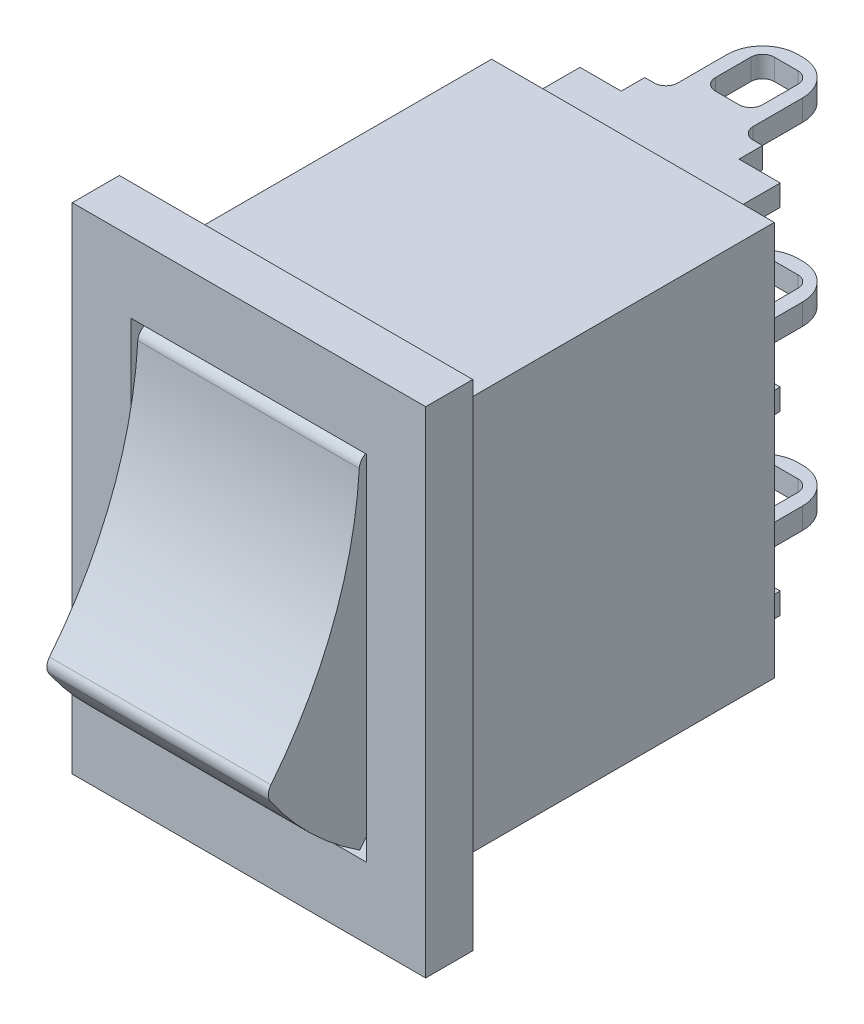
SolidWorks part; units mm, degrees
ref_plane "Frontal" through (0, 0, 0) normal (0, 0, 1) x (1, 0, 0)
ref_plane "Superior" through (0, 0, 0) normal (0, 1, 0) x (1, 0, 0)
ref_plane "Direito" through (0, 0, 0) normal (1, 0, 0) x (0, 0, -1)
sketch "Esboço1" plane through (0, 0, 0) normal (0, 0, 1) x (1, 0, 0)
  line L1 (-6, 8.375) -> (6, 8.375)
  line L2 (-6, 8.375) -> (-6, -8.375)
  line L3 (-6, -8.375) -> (6, -8.375)
  line L4 (6, 8.375) -> (6, -8.375)
  line L5 (-6, 8.375) -> (6, -8.375) construction
  line L6 (-6, -8.375) -> (6, 8.375) construction
  point P0 (0, 0)
  dimension "D1" = 16.75
  dimension "D2" = 12
extrude "Ressalto-extrusão1" add sketch "Esboço1" along normal blind 14.3
sketch "Esboço2" plane through (0, 0, 14.3) normal (0, 0, 1) x (1, 0, 0)
  line L1 (-7.5, 10.5) -> (7.5, 10.5)
  line L2 (-7.5, 10.5) -> (-7.5, -10.5)
  line L3 (-7.5, -10.5) -> (7.5, -10.5)
  line L4 (7.5, 10.5) -> (7.5, -10.5)
  line L5 (-7.5, 10.5) -> (7.5, -10.5) construction
  line L6 (-7.5, -10.5) -> (7.5, 10.5) construction
  point P0 (0, 0)
  dimension "D1" = 21
  dimension "D2" = 15
extrude "Ressalto-extrusão2" add sketch "Esboço2" along normal blind 2
sketch "Esboço3" plane through (0, 0, 16.3) normal (0, 0, 1) x (1, 0, 0)
  line L1 (-5, 7.5) -> (5, 7.5)
  line L2 (-5, 7.5) -> (-5, -7.5)
  line L3 (-5, -7.5) -> (5, -7.5)
  line L4 (5, 7.5) -> (5, -7.5)
  line L5 (-5, 7.5) -> (5, -7.5) construction
  line L6 (-5, -7.5) -> (5, 7.5) construction
  point P0 (0, 0)
  dimension "D1" = 10
  dimension "D2" = 15
extrude "Corte-extrusão1" cut sketch "Esboço3" against normal blind 10
sketch "Esboço4" plane through (0, 0, 0) normal (1, 0, 0) x (0, 0, -1)
  line L0 (-16.3, 0) -> (-20.3, 0) construction
  line L1 (-16.3, -10.5) -> (-16.3, 10.5) construction
  line L2 (-20.3, 0) -> (-20.3, -6.6626) construction
  line L3 (-16.3, 0) -> (-16.3, 7.2) construction
  line L4 (-16.3, 0) -> (-16.3, -7.2) construction
  line L5 (-16.3, -7.2) -> (-20.3, -7.2) construction
  line L6 (-20.3, -7.2) -> (-20.3, -3.2) construction
  line L7 (-17.4305, 1.6656) -> (-7.7474, -2.0587) construction
  arc A0 (-20.3, -3.2) -> (-16.3, -7.2) centre (-8.8669, 4.2331) ccw
  arc A1 (-16.3, 7.2) -> (-20.3, -3.2) centre (-33.414, 7.8131) cw
  arc A2 (-16.3, 7.2) -> (-10.6505, 7.4887) centre (-12.7945, -5.9787) cw
  arc A3 (-10.6505, 7.4887) -> (-16.3, -7.2) centre (-33.414, 7.8131) cw
  dimension "D1" = 4
  dimension "D2" = 4
extrude "Ressalto-extrusão3" add sketch "Esboço4" along normal blind 4.7 and the other way blind 4.7 contours A3 A2 A1 A0
fillet "Filete1" radius 0.5 2 edges at (0, 7.2, 16.3) (0, -3.2, 20.3)
sketch "Esboço5" plane through (0, 0, 0) normal (0, 0, -1) x (-1, 0, 0)
  line L0 (-4.25, 0) -> (4.25, 0) construction
  line L1 (-4.25, 0.45) -> (4.25, 0.45)
  line L2 (-4.25, 0.45) -> (-4.25, -0.45)
  line L3 (-4.25, -0.45) -> (4.25, -0.45)
  line L4 (4.25, 0.45) -> (4.25, -0.45)
  line L5 (-4.25, 0.45) -> (4.25, -0.45) construction
  line L6 (-4.25, -0.45) -> (4.25, 0.45) construction
  line L7 (0, 0) -> (0, 7.5) construction
  line L8 (0, 7.5) -> (0, -7.5) construction
  line L9 (-4.25, -7.95) -> (4.25, -7.95)
  line L10 (-4.25, -7.05) -> (4.25, -7.05)
  line L11 (-4.25, -7.5) -> (4.25, -7.5) construction
  line L12 (4.25, -7.05) -> (4.25, -7.95)
  line L13 (-4.25, -7.05) -> (-4.25, -7.95)
  line L14 (-4.25, -7.05) -> (4.25, -7.95) construction
  line L15 (-4.25, -7.95) -> (4.25, -7.05) construction
  line L16 (-4.25, 7.05) -> (4.25, 7.05)
  line L17 (-4.25, 7.95) -> (4.25, 7.95)
  line L18 (-4.25, 7.5) -> (4.25, 7.5) construction
  line L19 (4.25, 7.95) -> (4.25, 7.05)
  line L20 (-4.25, 7.95) -> (-4.25, 7.05)
  line L21 (-4.25, 7.95) -> (4.25, 7.05) construction
  line L22 (-4.25, 7.05) -> (4.25, 7.95) construction
  point P0 (0, 0)
  point P11 (0, -7.5)
  point P19 (0, 7.5)
extrude "Ressalto-extrusão4" add sketch "Esboço5" along normal blind 7.1
sketch "Esboço7" plane through (0, 0, 0) normal (0, 1, 0) x (1, 0, 0)
  line L0 (0, 0) -> (0, 7.1) construction
  line L1 (-4.25, 0) -> (-4.25, 2)
  line L2 (-4.25, 2) -> (-2.5, 2)
  line L3 (-2.5, 2) -> (-2.5, 3)
  line L4 (-4.25, 0) -> (4.25, 0)
  line L5 (-4.25, 7.1) -> (-4.25, 0)
  line L6 (4.25, 7.1) -> (-4.25, 7.1)
  line L7 (4.25, 0) -> (4.25, 7.1)
  line L8 (-4.25, 0) -> (4.25, 0) construction
  line L9 (-4.25, 7.1) -> (-4.25, 0)
  line L10 (4.25, 7.1) -> (-4.25, 7.1)
  line L11 (4.25, 0) -> (4.25, 7.1)
  line L12 (-2.5, 3) -> (-2.1, 3)
  line L13 (-1.6, 3.5) -> (-1.6, 5.6)
  line L14 (0, 6.5) -> (0, 4) construction
  line L15 (4.25, 0) -> (-4.25, 0)
  line L16 (1.6, 3.5) -> (1.6, 5.6)
  line L17 (2.5, 3) -> (2.1, 3)
  line L18 (2.5, 2) -> (2.5, 3)
  line L19 (4.25, 2) -> (2.5, 2)
  line L20 (4.25, 0) -> (4.25, 2)
  line L21 (0.5, 6.5) -> (-0.5, 6.5)
  line L22 (1, 6) -> (1, 4.5)
  line L23 (0.5, 4) -> (-0.5, 4)
  line L24 (-1, 6) -> (-1, 4.5)
  line L25 (0, 5.25) -> (0, 7.1) construction
  arc A0 (-1.6, 5.6) -> (-0.1, 7.1) centre (-0.1, 5.6) cw
  arc A1 (-2.1, 3) -> (-1.6, 3.5) centre (-2.1, 3.5) ccw
  arc A2 (2.1, 3) -> (1.6, 3.5) centre (2.1, 3.5) cw
  arc A3 (1.6, 5.6) -> (0.1, 7.1) centre (0.1, 5.6) ccw
  arc A4 (1, 4.5) -> (0.5, 4) centre (0.5, 4.5) cw
  arc A5 (-0.5, 4) -> (-1, 4.5) centre (-0.5, 4.5) cw
  arc A6 (-0.5, 6.5) -> (-1, 6) centre (-0.5, 6) ccw
  arc A7 (0.5, 6.5) -> (1, 6) centre (0.5, 6) cw
  point P13 (-1.6, 7.1)
  point P31 (0, 5.25)
  point P35 (1, 4)
  point P40 (-1, 6.5)
  point P43 (1, 6.5)
  dimension "D2" = 1.5
  dimension "D3" = 0.5
  dimension "D4" = 2.5
  dimension "D7" = 0.5
  dimension "D5" = 2
  dimension "D6" = 1.85
  dimension "D1" = 0
extrude "Corte-extrusão2" cut sketch "Esboço7" against normal through all and the other way through all contours A3 L16 A2 L17 L18 L19 L11 L10 | L12 A1 L13 A0 L10 L9 L2 L3 | A7 L21 A6 L24 A5 L23 A4 L22
